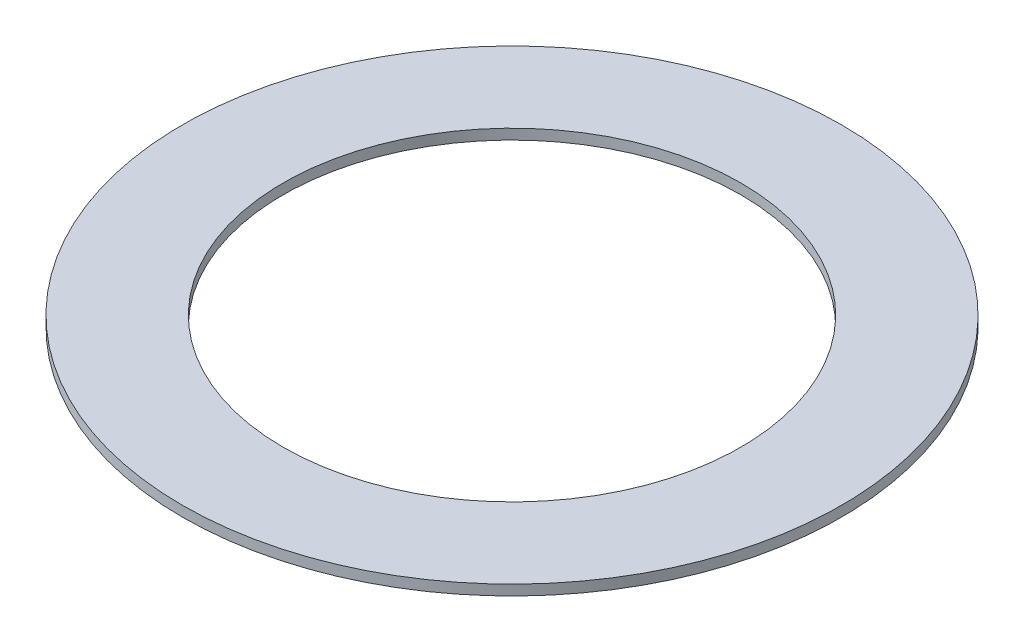
SolidWorks part; units mm, degrees
ref_plane "Front Plane" through (0, 0, 0) normal (0, 0, 1) x (1, 0, 0)
ref_plane "Top Plane" through (0, 0, 0) normal (0, 1, 0) x (1, 0, 0)
ref_plane "Right Plane" through (0, 0, 0) normal (1, 0, 0) x (0, 0, -1)
sketch "Sketch1" plane through (0, 0, 0) normal (0, 1, 0) x (1, 0, 0)
  circle A0 centre (0, 0) radius 5.5563
  circle A1 centre (0, 0) radius 8
  dimension "D1" = 11.1125
  dimension "D2" = 16
extrude "Boss-Extrude1" add sketch "Sketch1" along normal blind 0.25
